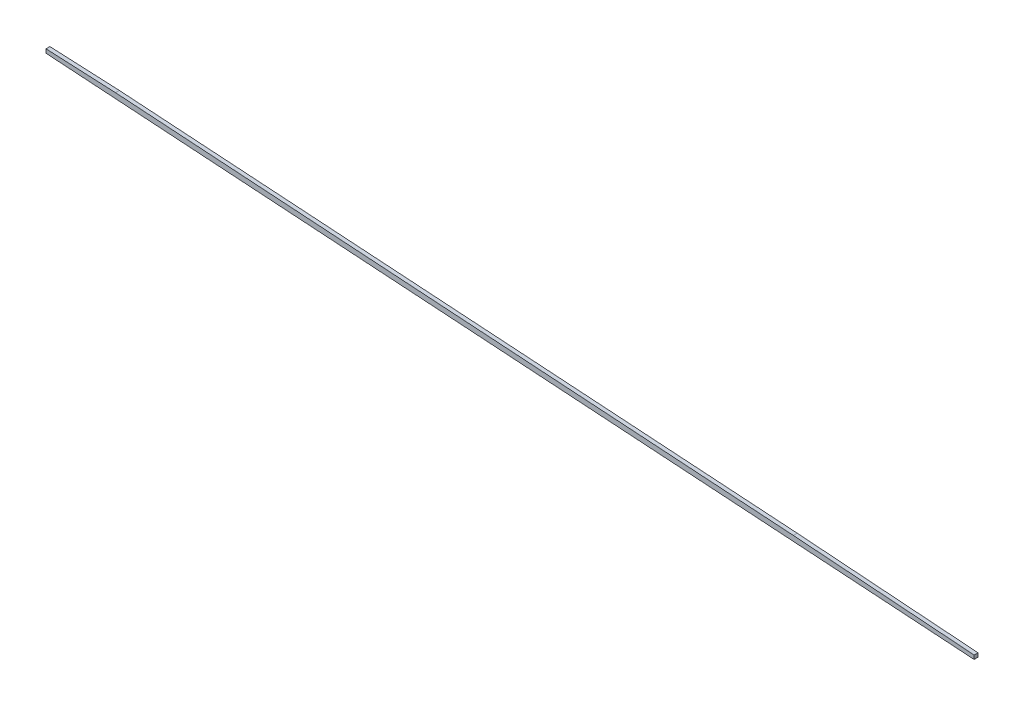
SolidWorks part; units mm, degrees
ref_plane "前视基准面" through (0, 0, 0) normal (0, 0, 1) x (1, 0, 0)
ref_plane "上视基准面" through (0, 0, 0) normal (0, 1, 0) x (1, 0, 0)
ref_plane "右视基准面" through (0, 0, 0) normal (1, 0, 0) x (0, 0, -1)
sketch "Model" plane through (0, 0, 0) normal (0, 0, 1) x (1, 0, 0)
  line L0 (-576.2583, 73.5637) -> (-532.4185, 70.6853)
  line L1 (-532.4185, 70.6853) -> (-516.3872, 69.6327)
  line L2 (-516.3872, 69.6327) -> (-472.5474, 66.7543)
  line L3 (-472.5474, 66.7543) -> (-356.731, 59.15)
  line L4 (-356.731, 59.15) -> (-163.2135, 46.4441)
  line L5 (-163.2135, 46.4441) -> (142.4732, 26.3734)
  line L6 (-576.2583, 76.5637) -> (-522.44, 74.0311)
  line L7 (-522.44, 74.0311) -> (-466.4947, 70.3579)
  line L8 (-466.4947, 70.3579) -> (-372.7623, 64.2036)
  line L9 (-372.7623, 64.2036) -> (2.4955, 39.565)
  line L10 (2.4955, 39.565) -> (142.5021, 29.3732)
  line L11 (142.4732, 26.3734) -> (142.5021, 29.3732)
  line L12 (-576.2583, 73.5637) -> (-576.2583, 76.5637)
extrude "凸台-拉伸1" add sketch "Model" along normal blind 3
